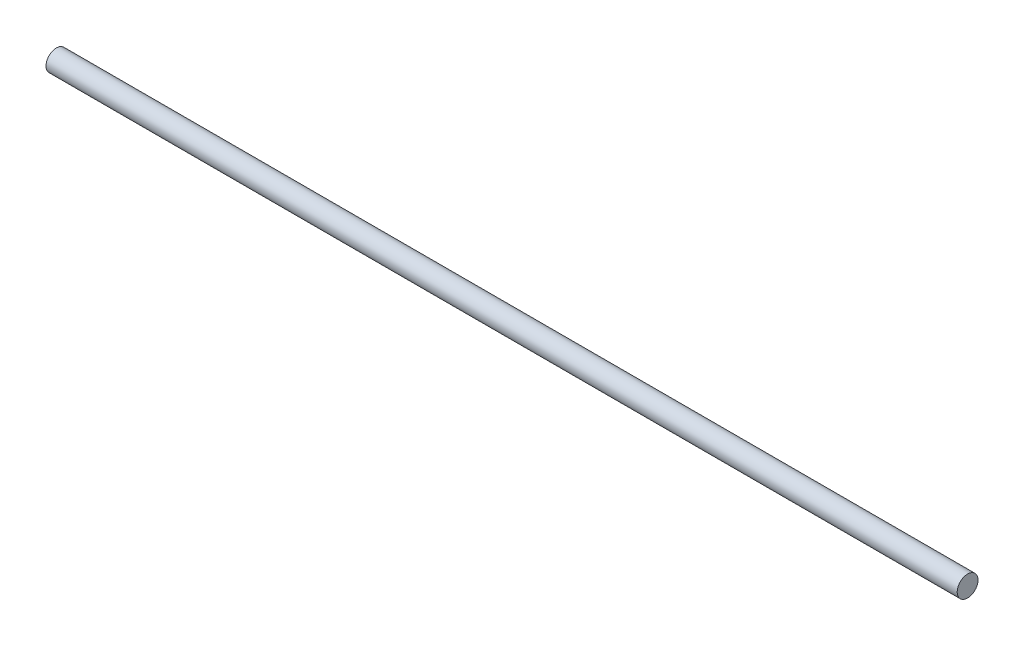
SolidWorks part; units mm, degrees
ref_plane "Front Plane" through (0, 0, 0) normal (0, 0, 1) x (1, 0, 0)
ref_plane "Top Plane" through (0, 0, 0) normal (0, 1, 0) x (1, 0, 0)
ref_plane "Right Plane" through (0, 0, 0) normal (1, 0, 0) x (0, 0, -1)
sketch "Sketch1" plane through (0, 0, 0) normal (0, 0, 1) x (1, 0, 0)
  line L1 (-175, -2) -> (175, -2)
  line L2 (-175, -2) -> (-175, 2)
  line L3 (-175, 2) -> (175, 2)
  line L4 (175, -2) -> (175, 2)
  line L5 (-175, -2) -> (175, 2) construction
  line L6 (-175, 2) -> (175, -2) construction
  point P0 (0, 0)
  dimension "D1" = 4
  dimension "D2" = 350
revolve "Revolve1" add sketch "Sketch1" angle 360 about L3
